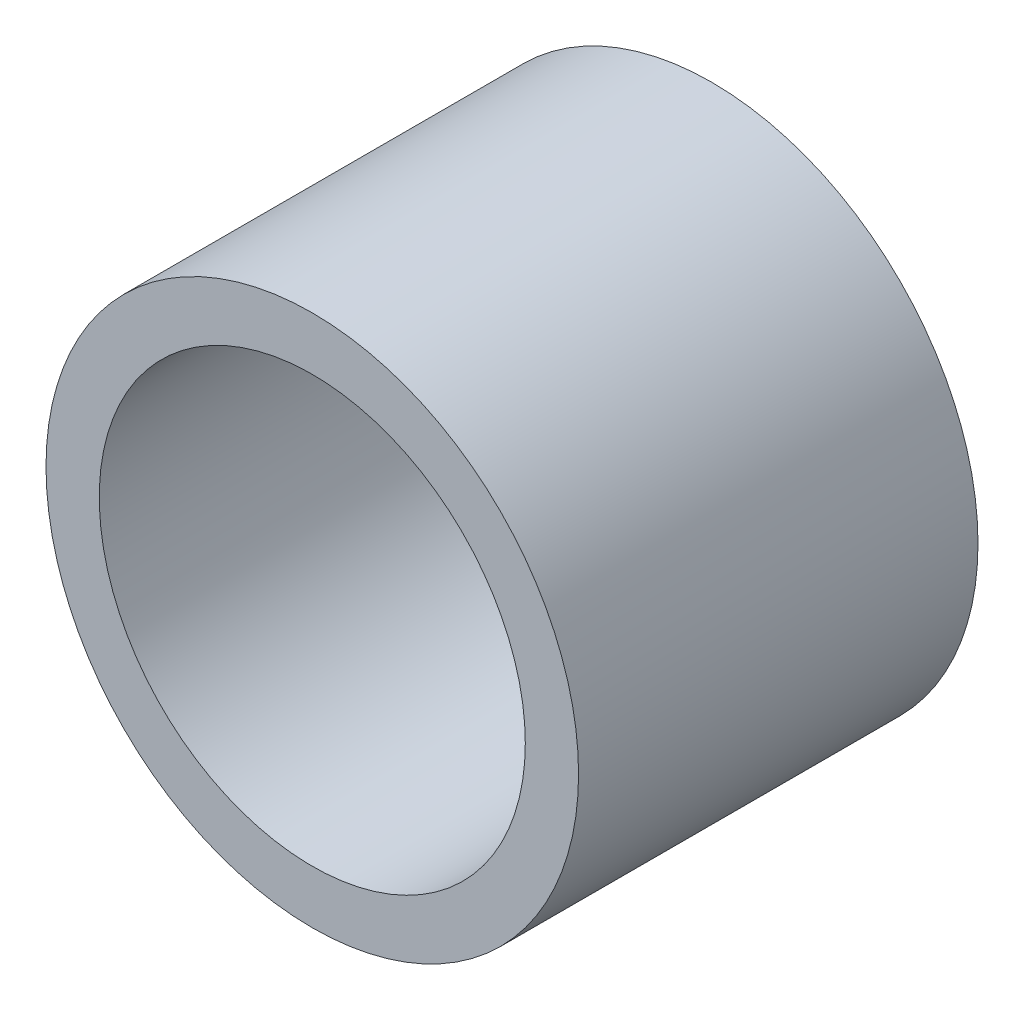
SolidWorks part; units mm, degrees
material "ABS PC"
ref_plane "Front Plane" through (0, 0, 0) normal (0, 0, 1) x (1, 0, 0)
ref_plane "Top Plane" through (0, 0, 0) normal (0, 1, 0) x (1, 0, 0)
ref_plane "Right Plane" through (0, 0, 0) normal (1, 0, 0) x (0, 0, -1)
sketch "Sketch1" plane through (0, 0, 0) normal (0, 0, 1) x (1, 0, 0)
  circle A0 centre (0, 0) radius 1.6
  circle A1 centre (0, 0) radius 2
  point P4 (0, 0)
  dimension "D1" = 3.2
  dimension "D2" = 4
extrude "Boss-Extrude1" add sketch "Sketch1" along normal blind 3
